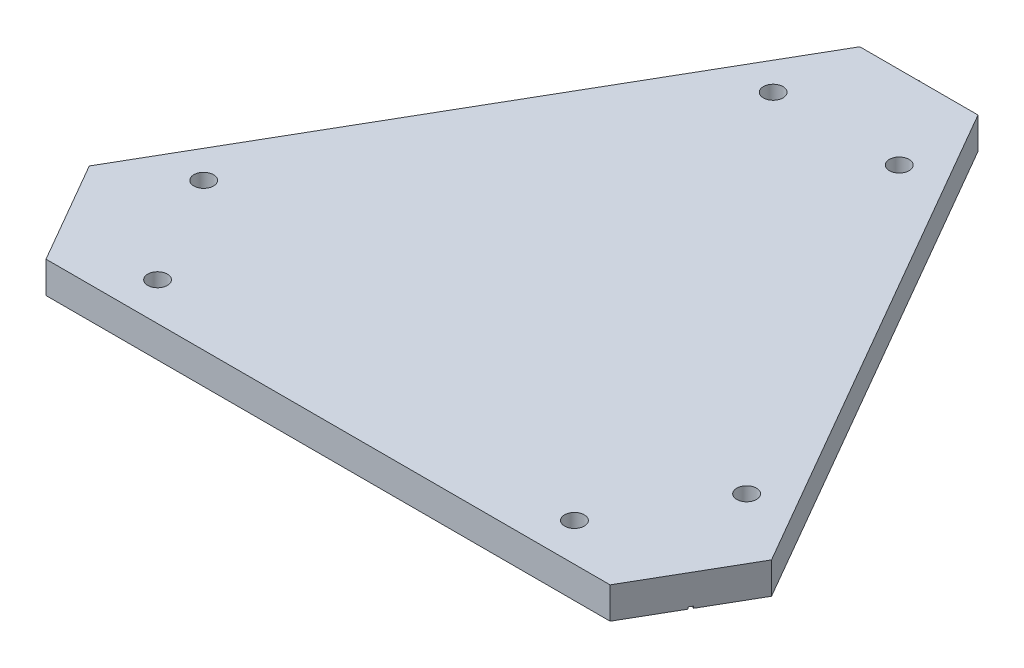
SolidWorks part; units mm, degrees
ref_plane "Alzado" through (0, 0, 0) normal (0, 0, 1) x (1, 0, 0)
ref_plane "Planta" through (0, 0, 0) normal (0, 1, 0) x (1, 0, 0)
ref_plane "Vista lateral" through (0, 0, 0) normal (1, 0, 0) x (0, 0, -1)
sketch "Croquis1" plane through (0, 0, 0) normal (0, 1, 0) x (1, 0, 0)
  line L8 (71.6025, 0) -> (86.6025, 25.9808)
  line L9 (-15, 150) -> (15, 150)
  line L15 (-86.6025, 25.9808) -> (-71.6025, 0)
  line L16 (-71.6025, 0) -> (71.6025, 0)
  line L17 (86.6025, 25.9808) -> (15, 150)
  line L18 (-15, 150) -> (-86.6025, 25.9808)
  line L19 (-129.0814, 0) -> (129.0814, 0) construction
  line L20 (0, -154.1098) -> (0, 154.1098) construction
  point P0 (0, 0)
  point P3 (0, 150)
  dimension "D2" = 0
  dimension "D3" = 0
  dimension "D5" = 30
  dimension "D6" = 30
  dimension "D7" = 30
  dimension "D8" = 150
  dimension "D9" = 150
  dimension "D10" = 150
extrude "Saliente-Extruir2" add sketch "Croquis1" along normal blind 8
sketch "Croquis3" plane through (0, 8, 0) normal (0, 1, 0) x (1, 0, 0)
  line L0 (-86.6025, 25.9808) -> (-71.6025, 0) construction
  line L1 (15, 150) -> (-15, 150) construction
  line L2 (0, -4.4) -> (0, 4.4) construction
  line L3 (-79.1025, 12.9904) -> (-85.2022, 9.4688) construction
  line L4 (71.6025, 0) -> (86.6025, 25.9808) construction
  line L5 (79.1025, 12.9904) -> (101.6025, 0) construction
  circle A2 centre (-16, 129) radius 2.5
  circle A3 centre (16, 129) radius 2.5
  circle A4 centre (-52.916, 9.634) radius 2.5
  circle A5 centre (-68.916, 37.3468) radius 2.5
  circle A6 centre (52.916, 9.634) radius 2.5
  circle A7 centre (68.916, 37.3468) radius 2.5
  dimension "D3" = 5
  dimension "D4" = 5
  dimension "D10" = 5
  dimension "D11" = 5
  dimension "D13" = 5
  dimension "D14" = 5
  dimension "D1" = 32
  dimension "D2" = 21
  dimension "D5" = 16
  dimension "D6" = 32
  dimension "D7" = 32
  dimension "D8" = 21
  dimension "D9" = 21
  dimension "D12" = 16
  dimension "D15" = 21
  dimension "D16" = 21
  dimension "D17" = 16
extrude "Cortar-Extruir1" cut sketch "Croquis3" against normal blind 31
sketch "Croquis4" plane through (0, 8, 0) normal (0, 1, 0) x (1, 0, 0)
  line L0 (15, 150) -> (-15, 150) construction
  line L1 (-0.05, 150.05) -> (0.05, 150.05)
  line L2 (-0.05, 150.05) -> (-0.05, 149.95)
  line L3 (-0.05, 149.95) -> (0.05, 149.95)
  line L4 (0.05, 150.05) -> (0.05, 149.95)
  line L5 (-0.05, 150.05) -> (0.05, 149.95) construction
  line L6 (-0.05, 149.95) -> (0.05, 150.05) construction
  point P0 (0, 150)
  dimension "D1" = 0.1
  dimension "D2" = 0.1
extrude "Saliente-Extruir3" add sketch "Croquis4" along normal blind 0.1
sketch "Croquis5" plane through (-53.7019, 0, 31.0048) normal (-0.866, 0, 0.5) x (0.5, 0, 0.866)
  line L0 (-65.8013, 0) -> (-35.8013, 0) construction
  line L1 (-51.3013, -0.437) -> (-50.3013, -0.437)
  line L2 (-51.3013, -0.437) -> (-51.3013, 0.437)
  line L3 (-51.3013, 0.437) -> (-50.3013, 0.437)
  line L4 (-50.3013, -0.437) -> (-50.3013, 0.437)
  line L5 (-51.3013, -0.437) -> (-50.3013, 0.437) construction
  line L6 (-51.3013, 0.437) -> (-50.3013, -0.437) construction
  line L7 (-65.8013, 8) -> (-65.8013, 0) construction
  point P0 (-50.8013, 0)
  dimension "D1" = 1
  dimension "D2" = 15
extrude "Cortar-Extruir2" cut sketch "Croquis5" against normal blind 10
sketch "Croquis6" plane through (53.7019, 0, 31.0048) normal (0.866, 0, 0.5) x (0.5, 0, -0.866)
  line L0 (82.5, 0) -> (-82.5, 0) construction
  line L1 (50.3013, -0.5) -> (51.3013, -0.5)
  line L2 (50.3013, -0.5) -> (50.3013, 0.5)
  line L3 (50.3013, 0.5) -> (51.3013, 0.5)
  line L4 (51.3013, -0.5) -> (51.3013, 0.5)
  line L5 (50.3013, -0.5) -> (51.3013, 0.5) construction
  line L6 (50.3013, 0.5) -> (51.3013, -0.5) construction
  line L8 (35.8013, 8) -> (35.8013, 0) construction
  point P0 (50.8013, 0)
  dimension "D1" = 1
  dimension "D2" = 1
  dimension "D3" = 15
extrude "Cortar-Extruir3" cut sketch "Croquis6" against normal blind 10
sketch "Croquis8" plane through (0, 0, -150) normal (0, 0, -1) x (-1, 0, 0)
  line L0 (82.5, 0) -> (-82.5, 0) construction
  line L1 (-0.5, -0.5) -> (0.5, -0.5)
  line L2 (-0.5, -0.5) -> (-0.5, 0.5)
  line L3 (-0.5, 0.5) -> (0.5, 0.5)
  line L4 (0.5, -0.5) -> (0.5, 0.5)
  line L5 (-0.5, -0.5) -> (0.5, 0.5) construction
  line L6 (-0.5, 0.5) -> (0.5, -0.5) construction
  line L7 (-15, 8) -> (-15, 0) construction
  point P0 (0, 0)
  dimension "D1" = 15
  dimension "D2" = 1
  dimension "D3" = 1
extrude "Cortar-Extruir4" cut sketch "Croquis8" against normal blind 10
